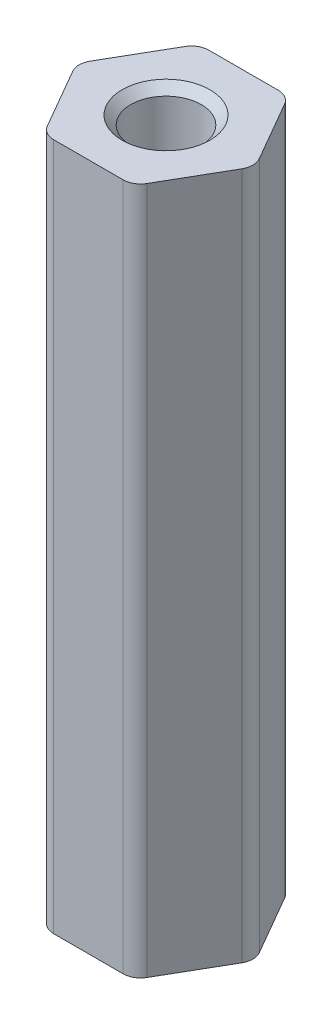
SolidWorks part; units mm, degrees
material "Brass"
ref_plane "Front Plane" through (0, 0, 0) normal (0, 0, 1) x (1, 0, 0)
ref_plane "Top Plane" through (0, 0, 0) normal (0, 1, 0) x (1, 0, 0)
ref_plane "Right Plane" through (0, 0, 0) normal (1, 0, 0) x (0, 0, -1)
sketch "Sketch1" plane through (0, 0, 0) normal (0, 1, 0) x (1, 0, 0)
  line L0 (0, 0) -> (2.6035, 0) construction
  line L1 (0, 0) -> (-2.6035, 0) construction
  line L2 (0, 0) -> (-1.3017, 2.2547) construction
  line L3 (0, 0) -> (1.3017, -2.2547) construction
  line L4 (0, 0) -> (1.3017, 2.2547) construction
  line L5 (0, 0) -> (-1.3017, -2.2547) construction
  line L6 (-2.6035, 0) -> (-1.3017, 2.2547)
  line L7 (-1.3017, 2.2547) -> (1.3017, 2.2547)
  line L8 (1.3017, 2.2547) -> (2.6035, 0)
  line L9 (2.6035, 0) -> (1.3017, -2.2547)
  line L10 (1.3017, -2.2547) -> (-1.3017, -2.2547)
  line L11 (-1.3017, -2.2547) -> (-2.6035, 0)
  dimension "D1" = 5.207
  dimension "D2" = 60
  dimension "D3" = 60
extrude "Boss-Extrude1" add sketch "Sketch1" along normal blind 19.9898 contours L7 L8 L9 L10 L11 L6
fillet "Fillet1" radius 0.508 6 edges at (-2.6035, 9.9949, 0) (-1.3017, 9.9949, 2.2547) (-1.3017, 9.9949, -2.2547) (1.3017, 9.9949, -2.2547) (2.6035, 9.9949, 0) (1.3017, 9.9949, 2.2547)
sketch "Sketch3" plane through (0, 19.9898, 0) normal (0, 1, 0) x (1, 0, 0)
  circle A0 centre (0, 0) radius 1.27
  dimension "D1" = 2.54
hole_wizard "M2.5x0.45 Tapped Hole1" positions "3DSketch1" profile "Sketch4" tap size "M2.5x0.45" standard "ANSI Metric" end condition through all
sketch3d "3DSketch1"
  point P0 (0, 19.9898, 0)
sketch "Sketch4" plane through (0, 19.9898, 0) normal (1, 0, 0) x (0, 0, 1)
  line L0 (0, 0) -> (0, 19.9898)
  line L1 (0, 19.9898) -> (1.025, 19.9898)
  line L2 (1.025, 19.9898) -> (1.025, 0.25)
  line L3 (1.025, 0.25) -> (1.275, 0)
  line L5 (1.275, 0) -> (0, 0)
  line L6 (-1.025, 0.25) -> (-1.275, 0) construction
  line L11 (0, -6.35) -> (0, 107.95) construction
  dimension "Thru Tap Drill Dia." = 2.05
  dimension "Thru Tap Drill Depth" = 19.9898
  dimension "Near C'Sink Dia." = 2.55
  dimension "Near C'Sink Angle" = 90
